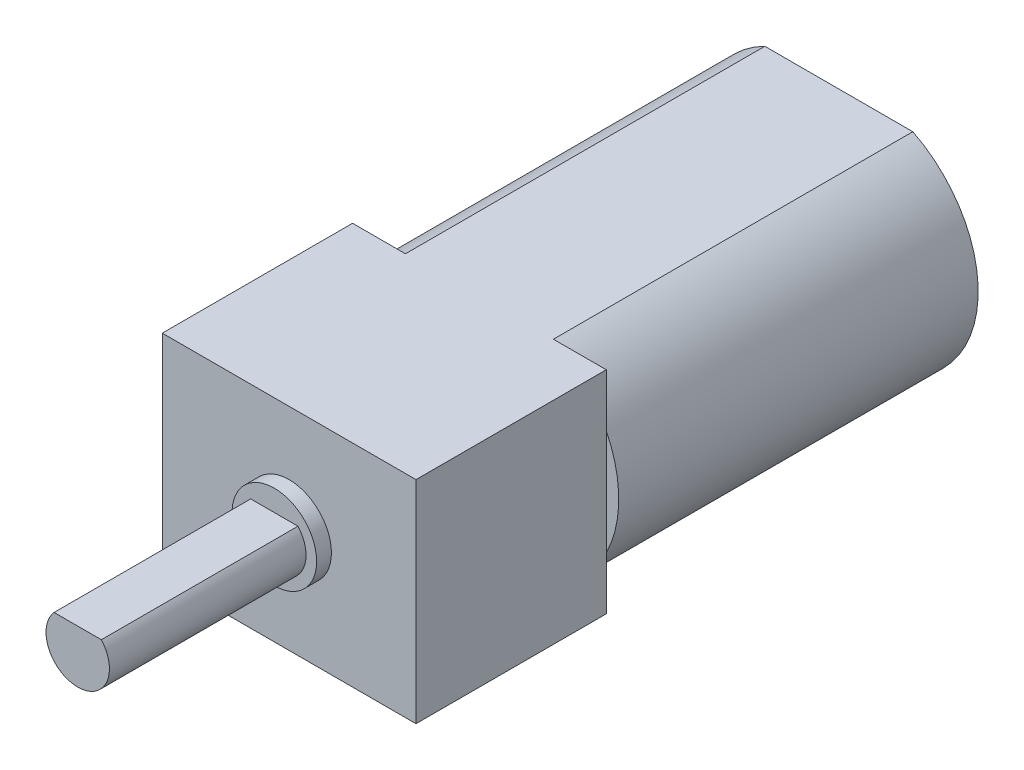
SolidWorks part; units mm, degrees
ref_plane "Plano frontal" through (0, 0, 0) normal (0, 0, 1) x (1, 0, 0)
ref_plane "Plano superior" through (0, 0, 0) normal (0, 1, 0) x (1, 0, 0)
ref_plane "Plano direito" through (0, 0, 0) normal (1, 0, 0) x (0, 0, -1)
sketch "Esboço1" plane through (0, 0, 0) normal (0, 0, 1) x (1, 0, 0)
  line L0 (-10.5763, 0) -> (12.3729, 0) construction
  line L1 (-3.5, 5) -> (3.5, 5)
  line L2 (0, -5) -> (0, 5) construction
  line L3 (-3.5, -5) -> (3.5, -5)
  arc A0 (3.5, 5) -> (3.5, -5) centre (1, 0) cw
  arc A1 (-3.5, 5) -> (-3.5, -5) centre (-1, 0) ccw
  point P8 (1.7288, 0)
  point P9 (7.1186, 0)
  point P10 (6.4407, 0)
  point P11 (2.5709, 0.6024)
  point P15 (0, 0)
  point P16 (2.5085, 0)
  dimension "D2" = 7
  dimension "D1" = 10
  dimension "D3" = 2
extrude "Ressalto-extrusão1" add sketch "Esboço1" against normal blind 17
sketch "Esboço2" plane through (0, 0, 0) normal (0, 0, 1) x (1, 0, 0)
  line L1 (-6, 5) -> (6, 5)
  line L2 (-6, 5) -> (-6, -5)
  line L3 (-6, -5) -> (6, -5)
  line L4 (6, 5) -> (6, -5)
  line L5 (-6, 5) -> (6, -5) construction
  line L6 (-6, -5) -> (6, 5) construction
  point P0 (0, 0)
  dimension "D1" = 10
  dimension "D2" = 12
extrude "Ressalto-extrusão2" add sketch "Esboço2" along normal blind 9
sketch "Esboço3" plane through (0, 0, 9) normal (0, 0, 1) x (1, 0, 0)
  circle A0 centre (0, 0) radius 2
  dimension "D1" = 4
extrude "Ressalto-extrusão3" add sketch "Esboço3" along normal blind 0.7
sketch "Esboço4" plane through (0, 0, 9.7) normal (0, 0, 1) x (1, 0, 0)
  circle A0 centre (0, 0) radius 1.5
  dimension "D1" = 3
extrude "Ressalto-extrusão4" add sketch "Esboço4" along normal blind 9.3
sketch "Esboço5" plane through (0, 0, 19) normal (0, 0, 1) x (1, 0, 0)
  line L0 (-1.118, 1) -> (1.118, 1)
  line L1 (0, 1) -> (0, -1.5) construction
  circle A0 centre (0, 0) radius 1.5 construction
  circle A1 centre (0, 0) radius 1.5 construction
  arc A2 (1.118, 1) -> (-1.118, 1) centre (0, 0) ccw
  dimension "D1" = 2.5
extrude "Corte-extrusão1" cut sketch "Esboço5" against normal up to surface (9.3 mm away) contours A2 L0 up to face at (1.5, 0, 9.7)
